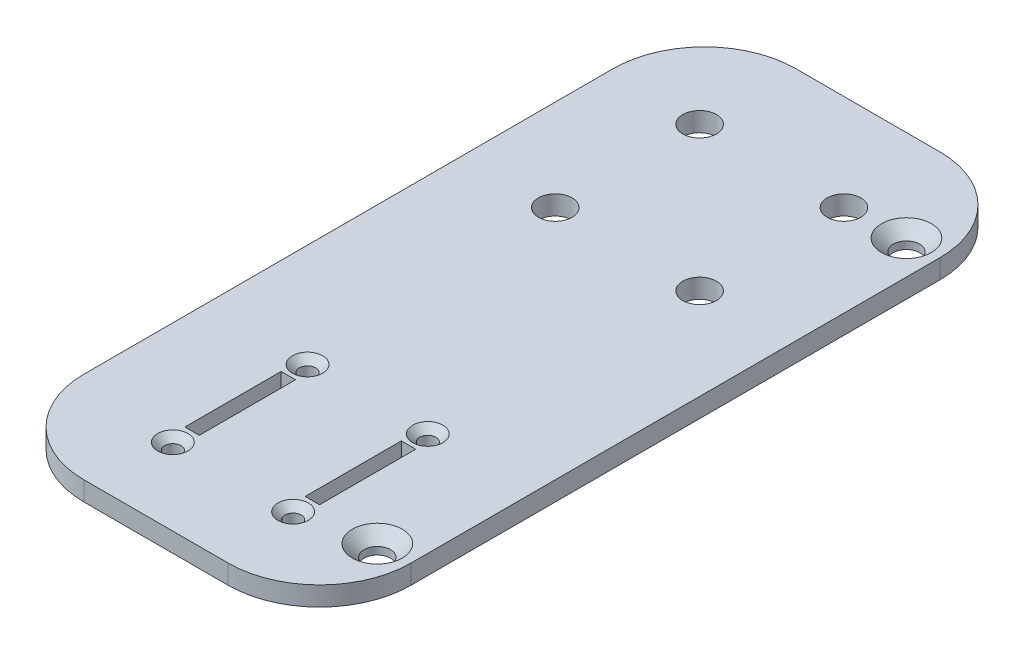
SolidWorks part; units mm, degrees
ref_plane "Front Plane" through (0, 0, 0) normal (0, 0, 1) x (1, 0, 0)
ref_plane "Top Plane" through (0, 0, 0) normal (0, 1, 0) x (1, 0, 0)
ref_plane "Right Plane" through (0, 0, 0) normal (1, 0, 0) x (0, 0, -1)
sketch "Sketch1" plane through (0, 0, 0) normal (0, 1, 0) x (1, 0, 0)
  line L0 (0, 74) -> (0, -74) construction
  line L1 (-15, -74) -> (15, -74)
  line L2 (-34, -55) -> (-34, 55)
  line L3 (-15, 74) -> (15, 74)
  line L4 (34, -55) -> (34, 55)
  line L5 (-34, -74) -> (34, 74) construction
  line L6 (-34, 74) -> (34, -74) construction
  line L7 (34, 0) -> (-34, 0) construction
  line L9 (-14, -54) -> (-11, -54)
  line L10 (-14, -54) -> (-14, -34)
  line L11 (-14, -34) -> (-11, -34)
  line L12 (-11, -54) -> (-11, -34)
  line L13 (-14, -54) -> (-11, -34) construction
  line L14 (-14, -34) -> (-11, -54) construction
  line L18 (34, 55) -> (27, 55) construction
  line L19 (27, 55) -> (27, -55) construction
  line L20 (27, -55) -> (34, -55) construction
  line L21 (14, -54) -> (11, -54)
  line L22 (14, -54) -> (14, -34)
  line L23 (14, -34) -> (11, -34)
  line L24 (11, -54) -> (11, -34)
  circle A0 centre (-15, 54) radius 3.5
  circle A1 centre (-15, 24) radius 3.5
  circle A2 centre (15, 24) radius 3.5
  circle A3 centre (15, 54) radius 3.5
  arc A4 (-34, -55) -> (-15, -74) centre (-15, -55) ccw
  arc A5 (34, -55) -> (15, -74) centre (15, -55) cw
  arc A6 (34, 55) -> (15, 74) centre (15, 55) ccw
  arc A7 (-34, 55) -> (-15, 74) centre (-15, 55) cw
  circle A8 centre (-12.5, -30) radius 1.5
  circle A9 centre (-12.5, -58) radius 1.5
  circle A12 centre (12.5, -30) radius 1.5
  circle A13 centre (12.5, -58) radius 1.5
  point P0 (0, 0)
  point P20 (-12.5, -44)
  dimension "D3" = 7
  dimension "D9" = 24
  dimension "D10" = 30
  dimension "D11" = 3
  dimension "D15" = 19
  dimension "D17" = 3
  dimension "D18" = 3
  dimension "D21" = 21.5
  dimension "D1" = 68
  dimension "D2" = 148
  dimension "D6" = 19
  dimension "D7" = 19
  dimension "D8" = 20
  dimension "D12" = 20
  dimension "D13" = 20
  dimension "D14" = 20
  dimension "D16" = 7
  dimension "D19" = 14
  dimension "D20" = 14
  dimension "D22" = 21.5
  dimension "D4" = 2
  dimension "D5" = 2
extrude "Boss-Extrude1" add sketch "Sketch1" along normal blind 4
hole_wizard "CSK for M5 Countersunk Flat Head1" positions "Sketch2" profile "Sketch3" countersink size "M5" standard "BSI" end condition up to next
sketch "Sketch2" plane through (0, 4, 0) normal (0, 1, 0) x (1, 0, 0)
  point P0 (27, 55)
  point P3 (27, -55)
sketch "Sketch3" plane through (27, 4, -55) normal (1, 0, 0) x (0, 0, 1)
  line L0 (0, 0) -> (0, 4)
  line L1 (0, 4) -> (2.75, 4)
  line L2 (2.75, 4) -> (2.75, 2.45)
  line L3 (2.75, 2.45) -> (5.2, 0)
  line L5 (5.2, 0) -> (0, 0)
  line L6 (-2.75, 2.45) -> (-5.2, 0) construction
  line L11 (0, -6.35) -> (0, 107.95) construction
  dimension "Thru Hole Dia." = 5.5
  dimension "Thru Hole Depth" = 4
  dimension "Near C'Sink Dia." = 10.4
  dimension "Near C'Sink Angle" = 90
hole_wizard "CSK for M3 Countersunk Flat Head1" positions "Sketch4" profile "Sketch5" countersink size "M3" standard "BSI" end condition up to next
sketch "Sketch4" plane through (0, 4, 0) normal (0, 1, 0) x (1, 0, 0)
  point P0 (-12.5, -30)
  point P3 (12.5, -30)
  point P6 (12.5, -58)
  point P9 (-12.5, -58)
sketch "Sketch5" plane through (-12.5, 4, 30) normal (1, 0, 0) x (0, 0, 1)
  line L0 (0, 0) -> (0, 4)
  line L1 (0, 4) -> (1.7, 4)
  line L2 (1.7, 4) -> (1.7, 1.45)
  line L3 (1.7, 1.45) -> (3.15, 0)
  line L5 (3.15, 0) -> (0, 0)
  line L6 (-1.7, 1.45) -> (-3.15, 0) construction
  line L11 (0, -6.35) -> (0, 107.95) construction
  dimension "Thru Hole Dia." = 3.4
  dimension "Thru Hole Depth" = 4
  dimension "Near C'Sink Dia." = 6.3
  dimension "Near C'Sink Angle" = 90
